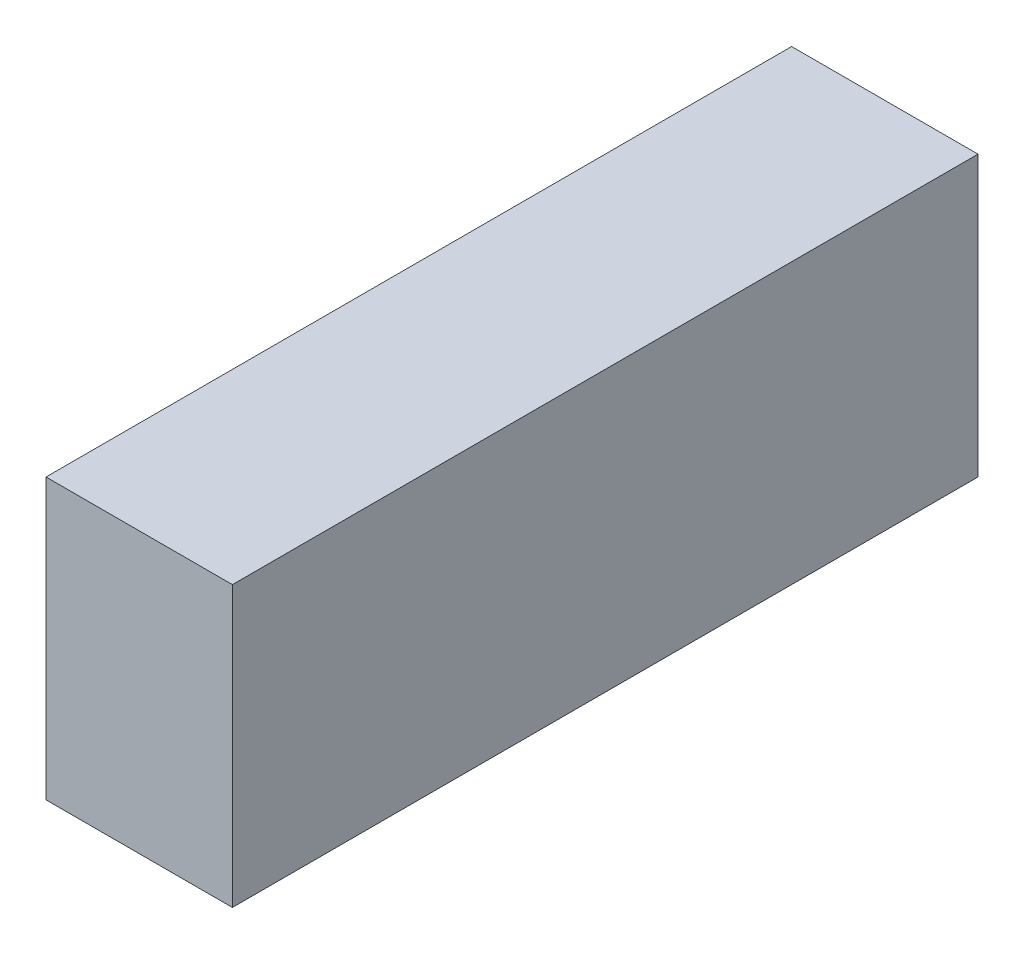
SolidWorks part; units mm, degrees
ref_plane "Front Plane" through (0, 0, 0) normal (0, 0, 1) x (1, 0, 0)
ref_plane "Top Plane" through (0, 0, 0) normal (0, 1, 0) x (1, 0, 0)
ref_plane "Right Plane" through (0, 0, 0) normal (1, 0, 0) x (0, 0, -1)
other "Configuration Table"
sketch "Sketch1" plane through (0, 0, 0) normal (0, 0, 1) x (1, 0, 0)
  line L1 (2, 29) -> (12, 29)
  line L2 (2, 29) -> (2, 44)
  line L3 (2, 44) -> (12, 44)
  line L4 (12, 29) -> (12, 44)
extrude "CEK_icecek_kayis_baglanti_pabucu_1" add sketch "Sketch1" against normal blind 40 from offset 40 separate body
